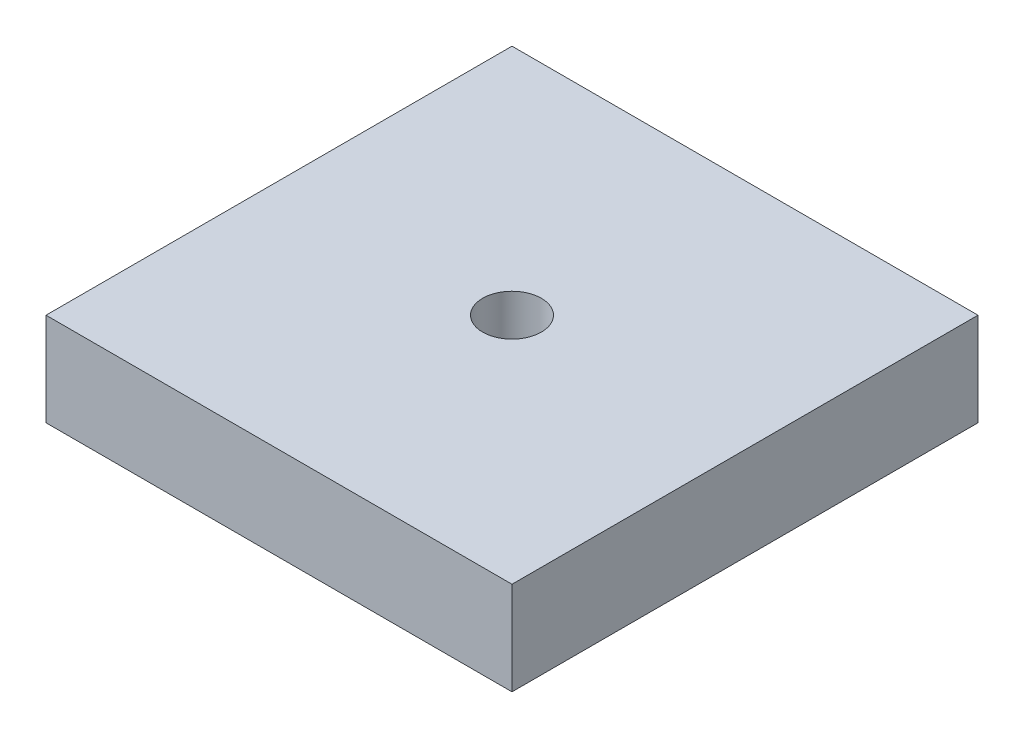
SolidWorks part; units mm, degrees
ref_plane "Front Plane" through (0, 0, 0) normal (0, 0, 1) x (1, 0, 0)
ref_plane "Top Plane" through (0, 0, 0) normal (0, 1, 0) x (1, 0, 0)
ref_plane "Right Plane" through (0, 0, 0) normal (1, 0, 0) x (0, 0, -1)
sketch "Sketch1" plane through (0, 0, 0) normal (0, 1, 0) x (1, 0, 0)
  line L1 (-25, 25) -> (25, 25)
  line L2 (-25, 25) -> (-25, -25)
  line L3 (-25, -25) -> (25, -25)
  line L4 (25, 25) -> (25, -25)
  line L5 (-25, 25) -> (25, -25) construction
  line L6 (-25, -25) -> (25, 25) construction
  point P0 (0, 0)
  dimension "D1" = 50
extrude "Boss-Extrude1" add sketch "Sketch1" along normal blind 10
sketch "Sketch2" plane through (0, 10, 0) normal (0, 1, 0) x (1, 0, 0)
  circle A0 centre (0, 0) radius 3.15
  dimension "D1" = 6.3
extrude "Cut-Extrude1" cut sketch "Sketch2" against normal blind 10 contours A0
